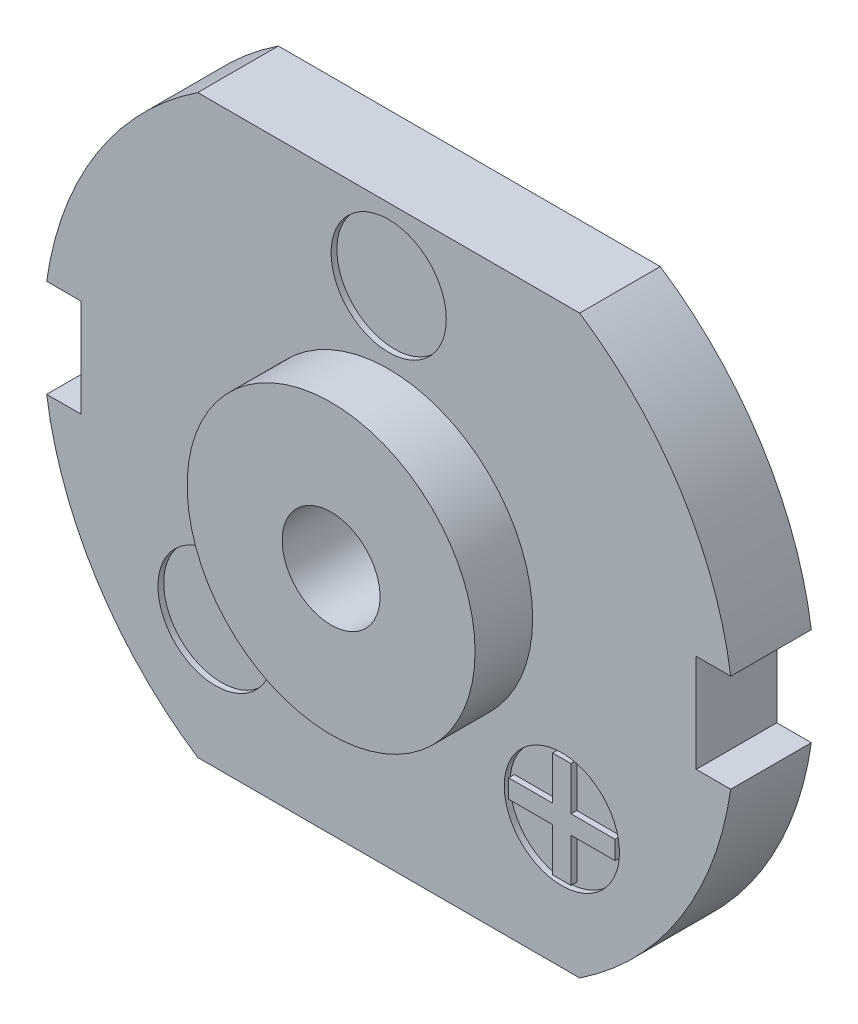
SolidWorks part; units mm, degrees
ref_plane "Front Plane" through (0, 0, 0) normal (0, 0, 1) x (1, 0, 0)
ref_plane "Top Plane" through (0, 0, 0) normal (0, 1, 0) x (1, 0, 0)
ref_plane "Right Plane" through (0, 0, 0) normal (1, 0, 0) x (0, 0, -1)
sketch "Sketch1" plane through (0, 0, 0) normal (0, 0, 1) x (1, 0, 0)
  line L0 (-5.3404, 0.85) -> (-5.9395, 0.85)
  line L1 (5.9395, -0.85) -> (5.3404, -0.85)
  line L2 (-3.3166, -5) -> (3.3166, -5)
  line L3 (3.3166, 5) -> (-3.3166, 5)
  line L4 (-3.3166, -5) -> (3.3166, -5)
  line L5 (3.3166, 5) -> (-3.3166, 5)
  line L7 (5.9395, 0.85) -> (5.3404, 0.85)
  line L8 (-5.3404, -0.85) -> (-5.9395, -0.85)
  line L12 (5.3404, -0.85) -> (5.3404, 0.85)
  line L14 (-5.3404, -0.85) -> (-5.3404, 0.85)
  arc A0 (-5.9395, -0.85) -> (-3.3166, -5) centre (0, 0) ccw
  arc A1 (5.9395, 0.85) -> (3.3166, 5) centre (0, 0) ccw
  arc A2 (-3.3166, 5) -> (-3.3166, -5) centre (0, 0) ccw
  arc A3 (3.3166, -5) -> (3.3166, 5) centre (0, 0) ccw
  arc A4 (-3.3166, 5) -> (-5.9395, 0.85) centre (0, 0) ccw
  arc A5 (3.3166, -5) -> (5.9395, -0.85) centre (0, 0) ccw
  circle A6 centre (0, 0) radius 0.85
  dimension "D2" = 1.7
  dimension "D1" = 0
extrude "Boss-Extrude1" add sketch "Sketch1" along normal blind 1.4
sketch "Sketch2" plane through (0, 0, 1.4) normal (0, 0, 1) x (1, 0, 0)
  circle A0 centre (0, 0) radius 2.5
  circle A1 centre (0, 0) radius 0.85 construction
  circle A2 centre (0, 0) radius 0.85
  dimension "D1" = 5
extrude "Boss-Extrude2" add sketch "Sketch2" along normal blind 1
sketch "Sketch3" plane through (0, 0, 1.4) normal (0, 0, 1) x (1, 0, 0)
  line L0 (3.1663, -2.606) -> (3.9305, -2.606)
  line L2 (2.847, -3.6834) -> (3.1663, -3.6834)
  line L3 (2.847, -3.6834) -> (2.847, -2.9278)
  line L4 (2.847, -1.8504) -> (3.1663, -1.8504)
  line L5 (3.1663, -3.6834) -> (3.1663, -2.9278)
  line L8 (2.0828, -2.9278) -> (2.847, -2.9278)
  line L9 (2.0828, -2.9278) -> (2.0828, -2.606)
  line L10 (2.0828, -2.606) -> (2.847, -2.606)
  line L11 (3.9305, -2.9278) -> (3.9305, -2.606)
  line L14 (3.1663, -2.606) -> (3.1663, -1.8504)
  line L16 (2.847, -2.606) -> (2.847, -1.8504)
  line L17 (3.1663, -2.9278) -> (3.9305, -2.9278)
  circle A1 centre (0, 3.75) radius 1
  circle A2 centre (-3.0067, -2.7669) radius 1
  circle A3 centre (3.0067, -2.7669) radius 1
  dimension "D1" = 2
extrude "Cut-Extrude1" cut sketch "Sketch3" against normal blind 0.1
